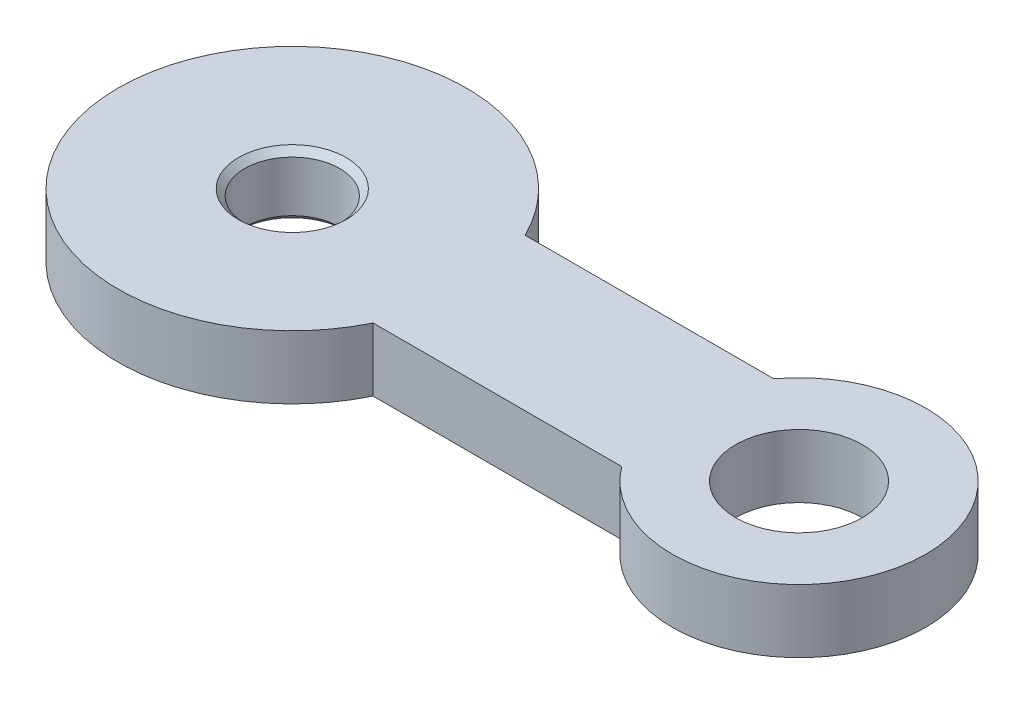
SolidWorks part; units mm, degrees
material "Brass"
ref_plane "Front Plane" through (0, 0, 0) normal (0, 0, 1) x (1, 0, 0)
ref_plane "Top Plane" through (0, 0, 0) normal (0, 1, 0) x (1, 0, 0)
ref_plane "Right Plane" through (0, 0, 0) normal (1, 0, 0) x (0, 0, -1)
sketch "Sketch1" plane through (0, 0, 0) normal (0, 1, 0) x (1, 0, 0)
  line L0 (31.4245, 15.24) -> (81.28, 15.24)
  line L1 (81.28, -15.24) -> (31.4245, -15.24)
  line L2 (0, 0) -> (101.6, 0) construction
  circle A0 centre (0, 0) radius 9.525
  arc A1 (31.4245, 15.24) -> (31.4245, -15.24) centre (0, 0) ccw
  circle A2 centre (101.6, 0) radius 12.7
  arc A3 (81.28, -15.24) -> (81.28, 15.24) centre (101.6, 0) ccw
  point P11 (25.0629, -15.24)
  point P12 (25.0629, 15.24)
  dimension "D1" = 25.4
  dimension "D2" = 19.05
  dimension "D3" = 25.4
  dimension "D4" = 50.8
  dimension "D5" = 15.24
  dimension "D6" = 15.24
  dimension "D7" = 101.6
extrude "Boss-Extrude1" add sketch "Sketch1" along normal blind 12.7
chamfer "Chamfer1" distance 1.27 angle 45 2 edges at (0, 0, 9.525) (0, 12.7, 9.525)
